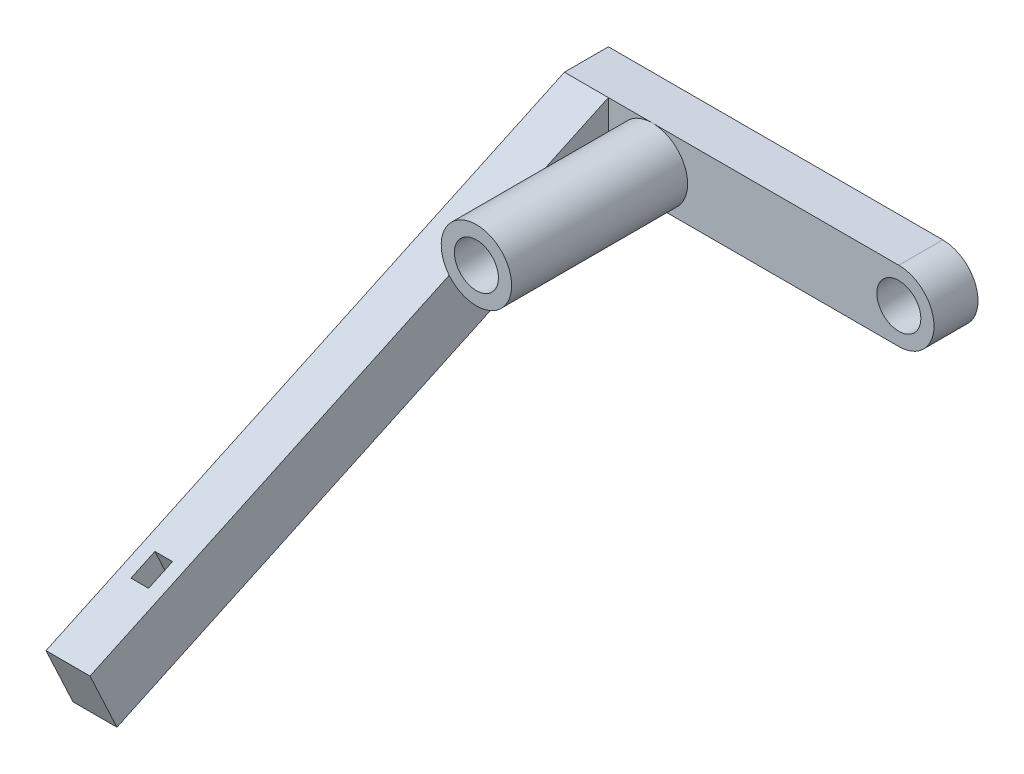
SolidWorks part; units mm, degrees
ref_plane "Alzado" through (0, 0, 0) normal (0, 0, 1) x (1, 0, 0)
ref_plane "Planta" through (0, 0, 0) normal (0, 1, 0) x (1, 0, 0)
ref_plane "Vista lateral" through (0, 0, 0) normal (1, 0, 0) x (0, 0, -1)
sketch "Croquis1" plane through (0, 0, 0) normal (0, 0, 1) x (1, 0, 0)
  line L0 (0, 0) -> (27.8544, 27.8544) construction
  line L1 (0, 0) -> (-42.4264, 42.4264) construction
  line L2 (0, 0) -> (0, 42.4264) construction
  line L3 (15.25, -15.25) -> (-15.25, -15.25) construction
  line L4 (15.25, -15.25) -> (15.25, 15.25) construction
  line L5 (15.25, 15.25) -> (-15.25, 15.25) construction
  line L6 (-15.25, -15.25) -> (-15.25, 15.25) construction
  line L7 (15.25, -15.25) -> (-15.25, 15.25) construction
  line L8 (15.25, 15.25) -> (-15.25, -15.25) construction
  line L9 (0, 42.4264) -> (-20, 42.4264) construction
  line L10 (-42.4264, 42.4264) -> (-38.8909, 45.9619)
  line L11 (-38.8909, 45.9619) -> (-31.0962, 38.1673)
  line L13 (-42.4264, 42.4264) -> (-45.9619, 38.8909)
  line L14 (-45.9619, 38.8909) -> (-38.1673, 31.0962)
  line L16 (38.8909, 45.9619) -> (31.0962, 38.1673)
  line L17 (42.4264, 42.4264) -> (38.8909, 45.9619)
  line L18 (42.4264, 42.4264) -> (45.9619, 38.8909)
  line L19 (-45.9619, -38.8909) -> (-38.1673, -31.0962)
  line L20 (0, 0) -> (-15.25, 0) construction
  line L21 (45.9619, 38.8909) -> (38.1673, 31.0962)
  line L22 (42.4264, -42.4264) -> (45.9619, -38.8909)
  line L23 (42.4264, -42.4264) -> (38.8909, -45.9619)
  line L24 (38.8909, -45.9619) -> (31.0962, -38.1673)
  line L27 (-38.8909, -45.9619) -> (-31.0962, -38.1673)
  line L28 (-42.4264, -42.4264) -> (-38.8909, -45.9619)
  line L29 (-42.4264, -42.4264) -> (-45.9619, -38.8909)
  line L30 (45.9619, -38.8909) -> (38.1673, -31.0962)
  line L31 (-15, 80) -> (15, 80) construction
  line L32 (0, -15.25) -> (0, -80) construction
  line L36 (-15, -80) -> (15, -80) construction
  line L105 (0, -80) -> (0, -83) construction
  line L106 (-15, -80) -> (0, -83)
  line L127 (15, -80) -> (0, -83)
  line L131 (0, 80) -> (0, 83) construction
  line L132 (-15, 80) -> (15, 80) construction
  line L136 (15, 80) -> (0, 83)
  line L157 (-15, 80) -> (0, 83)
  line L160 (-14, 30) -> (-17.8891, 33.8891) construction
  line L161 (-31.0962, 38.1673) -> (-22.6531, 29.7242)
  line L162 (-17.5359, 31.6883) -> (-15, 80)
  line L163 (17.5359, 31.6883) -> (15, 80)
  line L164 (31.0962, 38.1673) -> (22.6531, 29.7242)
  line L165 (31.0962, -38.1673) -> (22.6531, -29.7242)
  line L166 (17.5359, -31.6883) -> (15, -80)
  line L167 (-17.5359, -31.6883) -> (-15, -80)
  line L168 (-31.0962, -38.1673) -> (-22.6531, -29.7242)
  line L215 (-0.621, -15.7817) -> (-8.2129, -22.282)
  line L216 (-7.5625, -24.0416) -> (8.3607, -24.0416)
  line L217 (8.9758, -22.2532) -> (0.6445, -15.7529)
  line L218 (-7.5625, 24.0416) -> (8.3607, 24.0416)
  line L219 (8.9758, 22.2532) -> (0.6445, 15.7529)
  line L220 (-0.621, 15.7817) -> (-8.2129, 22.282)
  line L221 (-38.1673, 31.0962) -> (-28.2843, 21.2132)
  line L222 (-28.2843, -21.2132) -> (-38.1673, -31.0962)
  line L223 (28.2843, -21.2132) -> (38.1673, -31.0962)
  line L224 (38.1673, 31.0962) -> (28.2843, 21.2132)
  line L225 (0, -47.625) -> (0, -51.625) construction
  line L226 (0, -51.625) -> (16.4894, -51.625) construction
  line L227 (-10, -75) -> (-10, -70) construction
  line L232 (-10, -70) -> (10, -70)
  line L233 (10, -70) -> (0, -54.625)
  line L234 (0, -54.625) -> (-10, -70)
  line L235 (0, -48.625) -> (-10, -33.25)
  line L236 (10, -33.25) -> (0, -48.625)
  line L237 (-10, -33.25) -> (10, -33.25)
  line L238 (0, -51.625) -> (-16.4441, -52.4882) construction
  line L239 (-13.2359, -37.2991) -> (-11.7682, -65.2606)
  line L240 (-13.2359, -37.2991) -> (-3.7889, -51.8239)
  line L241 (-3.7889, -51.8239) -> (-11.7682, -65.2606)
  line L242 (3.7889, -51.8239) -> (11.7682, -65.2606)
  line L243 (13.2359, -37.2991) -> (3.7889, -51.8239)
  line L244 (13.2359, -37.2991) -> (11.7682, -65.2606)
  line L245 (0, 51.625) -> (-16.4441, 52.4882) construction
  line L246 (0, 51.625) -> (16.4894, 51.625) construction
  line L247 (0, 47.625) -> (0, 51.625) construction
  line L248 (13.2359, 37.2991) -> (11.7682, 65.2606)
  line L249 (13.2359, 37.2991) -> (3.7889, 51.8239)
  line L250 (3.7889, 51.8239) -> (11.7682, 65.2606)
  line L251 (-3.7889, 51.8239) -> (-11.7682, 65.2606)
  line L252 (-13.2359, 37.2991) -> (-3.7889, 51.8239)
  line L253 (-13.2359, 37.2991) -> (-11.7682, 65.2606)
  line L254 (-10, 33.25) -> (10, 33.25)
  line L255 (10, 33.25) -> (0, 48.625)
  line L256 (0, 48.625) -> (-10, 33.25)
  line L257 (0, 54.625) -> (-10, 70)
  line L258 (10, 70) -> (0, 54.625)
  line L259 (-10, 70) -> (10, 70)
  circle A0 centre (-15.25, 15.25) radius 4
  circle A1 centre (-24.0416, 24.0416) radius 1.5
  circle A2 centre (-38.8909, 38.8909) radius 1.5
  circle A5 centre (38.8909, 38.8909) radius 1.5
  circle A6 centre (24.0416, 24.0416) radius 1.5
  circle A7 centre (15.25, 15.25) radius 4
  circle A8 centre (15.25, -15.25) radius 4
  circle A9 centre (24.0416, -24.0416) radius 1.5
  circle A10 centre (38.8909, -38.8909) radius 1.5
  circle A12 centre (-15.25, -15.25) radius 4
  circle A13 centre (-24.0416, -24.0416) radius 1.5
  circle A14 centre (-38.8909, -38.8909) radius 1.5
  circle A18 centre (0, 0) radius 3.5
  circle A19 centre (-11.5, -75) radius 1.5
  circle A21 centre (-14, 30) radius 1.5
  circle A111 centre (11.5, -75) radius 1.5
  circle A112 centre (11.5, 75) radius 1.5
  circle A137 centre (-11.5, 75) radius 1.5
  arc A138 (-22.6531, 29.7242) -> (-17.5359, 31.6883) centre (-20.5318, 31.8455) ccw
  arc A139 (22.6531, 29.7242) -> (17.5359, 31.6883) centre (20.5318, 31.8455) cw
  arc A140 (22.6531, -29.7242) -> (17.5359, -31.6883) centre (20.5318, -31.8455) ccw
  arc A141 (-22.6531, -29.7242) -> (-17.5359, -31.6883) centre (-20.5318, -31.8455) cw
  circle A142 centre (14, 30) radius 1.5
  circle A143 centre (14, -30) radius 1.5
  circle A144 centre (-14, -30) radius 1.5
  arc A191 (8.3607, -24.0416) -> (8.9758, -22.2532) centre (8.3607, -23.0416) ccw
  arc A192 (0.6445, -15.7529) -> (-0.621, -15.7817) centre (0.0294, -16.5413) ccw
  arc A193 (-8.2129, -22.282) -> (-7.5625, -24.0416) centre (-7.5625, -23.0416) ccw
  arc A194 (8.3607, 24.0416) -> (8.9758, 22.2532) centre (8.3607, 23.0416) cw
  arc A195 (0.6445, 15.7529) -> (-0.621, 15.7817) centre (0.0294, 16.5413) cw
  arc A196 (-8.2129, 22.282) -> (-7.5625, 24.0416) centre (-7.5625, 23.0416) cw
  arc A197 (-28.2843, 21.2132) -> (-28.2843, -21.2132) centre (-49.4975, 0) cw
  arc A198 (28.2843, 21.2132) -> (28.2843, -21.2132) centre (49.4975, 0) ccw
  circle A199 centre (0, 76) radius 1
  circle A200 centre (0, -76) radius 1
  point P35 (-34.9935, 42.0646)
  point P37 (44.1942, 40.6586)
  point P45 (44.1942, -40.6586)
  point P61 (-34.9935, -42.0646)
  point P70 (0, 80)
  point P260 (-7.0711, 0)
  dimension "D2" = 8
  dimension "D4" = 5
  dimension "D8" = 14.75
  dimension "D10" = 3
  dimension "D11" = 3
  dimension "D13" = 11.5
  dimension "D15" = 3
  dimension "D16" = 14
  dimension "D18" = 3
  dimension "D24" = 3
  dimension "D26" = 1
  dimension "D27" = 7
  dimension "D28" = 30
  dimension "D29" = 7
  dimension "D1" = 30.5
  dimension "D3" = 60
  dimension "D5" = 21
  dimension "D6" = 15
  dimension "D7" = 5
  dimension "D9" = 5
  dimension "D12" = 80
  dimension "D14" = 5
  dimension "D17" = 5
  dimension "D19" = 28.375
  dimension "D20" = 3
  dimension "D21" = 4
  dimension "D22" = 15
  dimension "D25" = 13
  dimension "D23" = 5.5
extrude "Saliente-Extruir1" add sketch "Croquis1" along normal blind 2
fillet "Redondeo1" radius 3 12 edges at (45.9619, -38.8909, 1) (38.8909, -45.9619, 1) (-45.9619, -38.8909, 1) (-38.8909, -45.9619, 1) (45.9619, 38.8909, 1) (38.8909, 45.9619, 1) (-38.8909, 45.9619, 1) (-45.9619, 38.8909, 1) (15, 80, 1) (-15, 80, 1) (15, -80, 1) (-15, -80, 1)
fillet "Redondeo2" radius 10 2 edges at (0, -83, 1) (0, 83, 1)
fillet "Redondeo3" radius 2 24 edges at (10, 70, 1) (-10, 70, 1) (13.2359, 37.2991, 1) (10, 33.25, 1) (-10, 33.25, 1) (-13.2359, 37.2991, 1) (-11.7682, 65.2606, 1) (0, 54.625, 1) (3.7889, 51.8239, 1) (0, 48.625, 1) (-3.7889, 51.8239, 1) (11.7682, -65.2606, 1) (3.7889, -51.8239, 1) (13.2359, -37.2991, 1) (10, -33.25, 1) (0, -48.625, 1) (-10, -33.25, 1) (10, -70, 1) (0, -54.625, 1) (-10, -70, 1) (-11.7682, -65.2606, 1) (-3.7889, -51.8239, 1) (-13.2359, -37.2991, 1) (11.7682, 65.2606, 1)
sketch "Croquis2" plane through (0, 0, 2) normal (0, 0, 1) x (1, 0, 0)
  line L3 (14, 34) -> (-14, 34)
  line L10 (-14, 34) -> (-24, 34)
  line L11 (-24, 34) -> (-24, 26)
  line L12 (-24, 26) -> (-14, 26)
  line L13 (14, 26) -> (-14, 26)
  line L14 (-6.3134, 33.25) -> (6.3134, 33.25) construction
  circle A0 centre (-14, 30) radius 2.5
  arc A4 (14, 34) -> (14, 26) centre (14, 30) cw
  circle A5 centre (14, 30) radius 2.5
  point P15 (0, 21)
  dimension "D1" = 5
  dimension "D2" = 10
extrude "Saliente-Extruir2" add sketch "Croquis2" along normal blind 5
sketch "Croquis3" plane through (0, 0, 2) normal (0, 0, 1) x (1, 0, 0)
  line L1 (-81.2329, 100.1452) -> (76.5368, 100.1452)
  line L2 (-81.2329, 100.1452) -> (-81.2329, -95.7815)
  line L3 (-81.2329, -95.7815) -> (76.5368, -95.7815)
  line L4 (76.5368, 100.1452) -> (76.5368, -95.7815)
extrude "Cortar-Extruir1" cut sketch "Croquis3" against normal up to vertex
sketch "Croquis6" plane through (-24, 0, 0) normal (-1, 0, 0) x (0, 0, 1)
  line L0 (2, 26) -> (20.045, 17.5855)
  line L1 (7, 26) -> (2, 26) construction
  dimension "D1" = 25
sketch "Croquis9" plane through (0, 0, 7) normal (0, 0, 1) x (1, 0, 0)
  line L0 (-24, 26) -> (14, 26) construction
  line L1 (-24, 34) -> (-19, 34)
  line L2 (-24, 34) -> (-24, 26)
  line L3 (-24, 26) -> (-19, 26)
  line L4 (-19, 34) -> (-19, 26)
  dimension "D1" = 5
extrude "Saliente-Extruir8" add sketch "Croquis9" along direction (0, -0.4226, 0.9063) on the side of the normal blind 65
sketch "Croquis10" plane through (-24, 0, 0) normal (-1, 0, 0) x (0, 0, 1)
  line L0 (65.91, 6.5298) -> (62.8458, -0.0413)
  line L1 (65.91, -1.4702) -> (7, 26) construction
  line L2 (62.8458, -0.0413) -> (65.91, -1.4702)
  line L3 (65.91, -1.4702) -> (65.91, 6.5298)
  dimension "D3" = 25
extrude "Cortar-Extruir2" cut sketch "Croquis10" against normal up to vertex (5 mm away) up to point (-19, 6.5298, 65.91)
sketch "Croquis11" plane through (0, 24.0374, 11.2088) normal (0, -0.9063, -0.4226) x (1, 0, 0)
  line L0 (-24, 56.9751) -> (-24, -4.6439) construction
  line L1 (-22.5, 47.9751) -> (-20.5, 47.9751)
  line L2 (-22.5, 47.9751) -> (-22.5, 44.9751)
  line L3 (-22.5, 44.9751) -> (-20.5, 44.9751)
  line L4 (-20.5, 47.9751) -> (-20.5, 44.9751)
  line L6 (-19, 56.9751) -> (-24, 56.9751) construction
  dimension "D1" = 2
  dimension "D2" = 3
  dimension "D3" = 1.5
  dimension "D4" = 9
extrude "Cortar-Extruir3" cut sketch "Croquis11" against normal up to vertex (7.2505 mm away)
sketch "Croquis12" plane through (0, 0, 7) normal (0, 0, 1) x (1, 0, 0)
  circle A0 centre (-14, 30) radius 2.5
  circle A1 centre (-14, 30) radius 4
extrude "Saliente-Extruir9" add sketch "Croquis12" along normal blind 20
ref_plane "Plano1" through (0, 0, 0) normal (-1, 0, 0) x (0, 0, 1)
